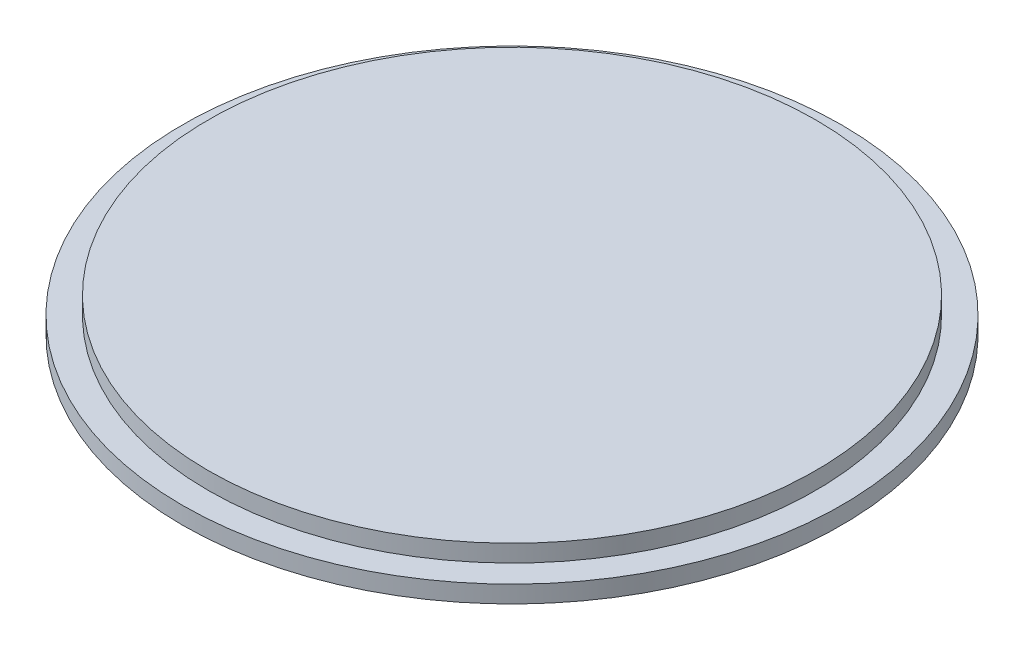
SolidWorks part; units mm, degrees
ref_plane "Front Plane" through (0, 0, 0) normal (0, 0, 1) x (1, 0, 0)
ref_plane "Top Plane" through (0, 0, 0) normal (0, 1, 0) x (1, 0, 0)
ref_plane "Right Plane" through (0, 0, 0) normal (1, 0, 0) x (0, 0, -1)
sketch "Sketch2" plane through (0, 0, 0) normal (0, 1, 0) x (1, 0, 0)
  circle A0 centre (0, 0) radius 57.5
  dimension "D1" = 115
extrude "Boss-Extrude1" add sketch "Sketch2" along normal blind 3
sketch "Sketch3" plane through (0, 3, 0) normal (0, 1, 0) x (1, 0, 0)
  circle A0 centre (0, 0) radius 53
  dimension "D1" = 106
extrude "Boss-Extrude2" add sketch "Sketch3" along normal blind 3
